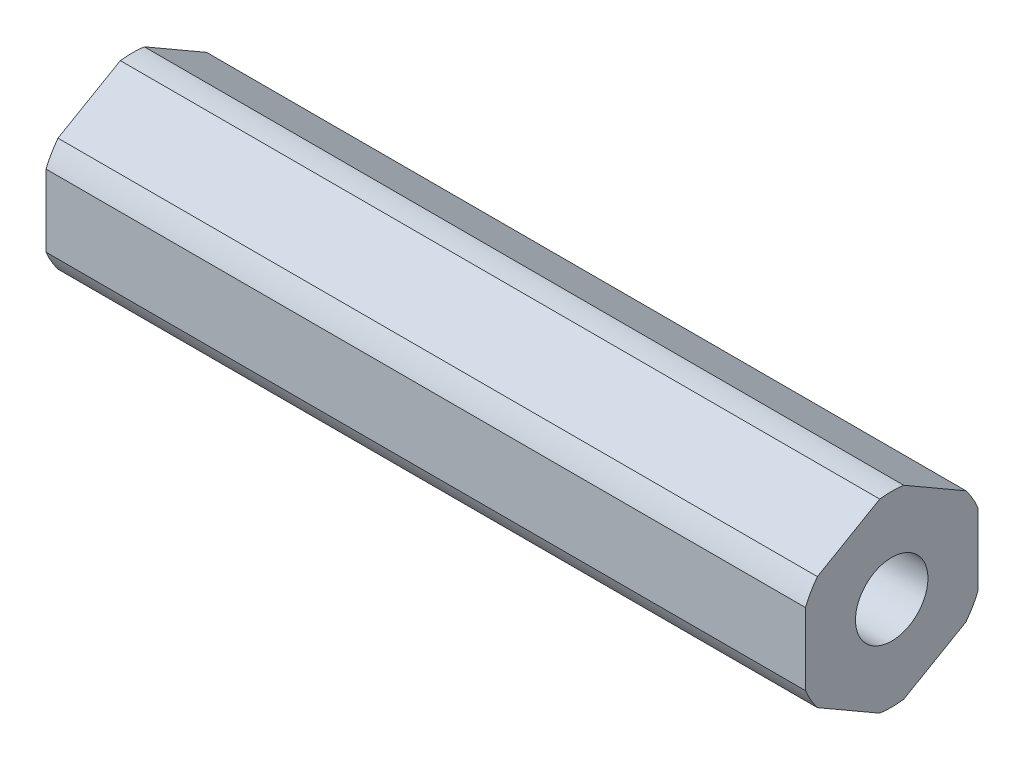
SolidWorks part; units mm, degrees
ref_plane "Front Plane" through (0, 0, 0) normal (0, 0, 1) x (1, 0, 0)
ref_plane "Top Plane" through (0, 0, 0) normal (0, 1, 0) x (1, 0, 0)
ref_plane "Right Plane" through (0, 0, 0) normal (1, 0, 0) x (0, 0, -1)
ref_plane "Plane1" through (-41.275, 0, 0) normal (-1, 0, 0) x (0, -1, 0)
sketch "Sketch1" plane through (-41.275, 0, 0) normal (-1, 0, 0) x (0, -1, 0)
  line L0 (4.1753, -5.4682) -> (6.8233, -0.8818)
  line L1 (6.8233, 0.8818) -> (4.1753, 5.4682)
  line L2 (2.648, 6.35) -> (-2.648, 6.35)
  line L3 (-4.1753, 5.4682) -> (-6.8233, 0.8818)
  line L4 (-6.8233, -0.8818) -> (-4.1753, -5.4682)
  line L5 (-2.648, -6.35) -> (2.648, -6.35)
  circle A0 centre (0, 0) radius 2.667
  arc A1 (2.648, -6.35) -> (4.1753, -5.4682) centre (0, 0) ccw
  arc A2 (6.8233, -0.8818) -> (6.8233, 0.8818) centre (0, 0) ccw
  arc A3 (4.1753, 5.4682) -> (2.648, 6.35) centre (0, 0) ccw
  arc A4 (-2.648, 6.35) -> (-4.1753, 5.4682) centre (0, 0) ccw
  arc A5 (-6.8233, 0.8818) -> (-6.8233, -0.8818) centre (0, 0) ccw
  arc A6 (-4.1753, -5.4682) -> (-2.648, -6.35) centre (0, 0) ccw
extrude "Boss-Extrude1" add sketch "Sketch1" against normal blind 55.88
